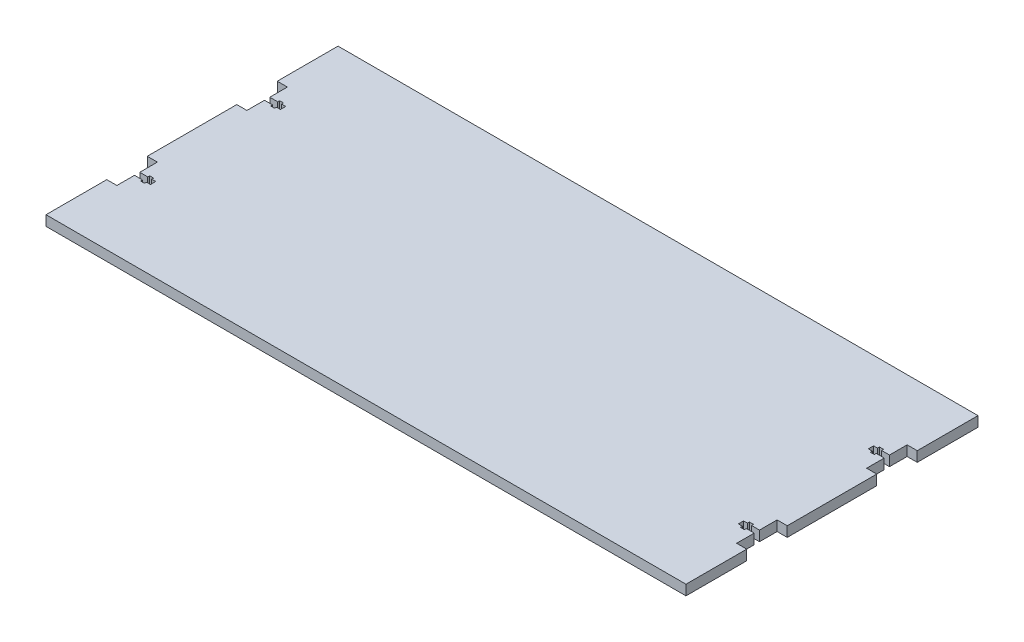
SolidWorks part; units mm, degrees
material "Pine"
ref_plane "Front Plane" through (0, 0, 0) normal (0, 0, 1) x (1, 0, 0)
ref_plane "Top Plane" through (0, 0, 0) normal (0, 1, 0) x (1, 0, 0)
ref_plane "Right Plane" through (0, 0, 0) normal (1, 0, 0) x (0, 0, -1)
ref_plane "Plane1" through (0, 365.1, 0) normal (0, -1, 0) x (1, 0, 0)
sketch "Sketch1" plane through (0, 365.1, 0) normal (0, -1, 0) x (1, 0, 0)
  line L0 (-388.62, -123.4119) -> (-382.27, -123.4119)
  line L1 (-382.27, -123.4119) -> (-382.27, -134.4619)
  line L2 (-382.27, -134.4619) -> (-377.27, -134.4619)
  line L3 (-377.27, -134.4619) -> (-377.27, -133.2619)
  line L4 (-377.27, -133.2619) -> (-374.77, -133.2619)
  line L5 (-374.77, -133.2619) -> (-374.77, -134.4619)
  line L6 (-374.77, -134.4619) -> (-372.27, -134.4619)
  line L7 (-372.27, -134.4619) -> (-372.27, -137.7619)
  line L8 (-372.27, -137.7619) -> (-374.77, -137.7619)
  line L9 (-374.77, -137.7619) -> (-374.77, -138.9619)
  line L10 (-374.77, -138.9619) -> (-377.27, -138.9619)
  line L11 (-377.27, -138.9619) -> (-377.27, -137.7619)
  line L12 (-377.27, -137.7619) -> (-382.27, -137.7619)
  line L13 (-382.27, -137.7619) -> (-382.27, -148.8119)
  line L14 (-382.27, -148.8119) -> (-388.62, -148.8119)
  line L15 (-388.62, -148.8119) -> (-388.62, -186.9119)
  line L16 (-388.62, -186.9119) -> (12.7, -186.9119)
  line L17 (12.7, -186.9119) -> (12.7, -148.8119)
  line L18 (12.7, -148.8119) -> (6.35, -148.8119)
  line L19 (6.35, -148.8119) -> (6.35, -137.7619)
  line L20 (6.35, -137.7619) -> (1.35, -137.7619)
  line L21 (1.35, -137.7619) -> (1.35, -138.9619)
  line L22 (1.35, -138.9619) -> (-1.15, -138.9619)
  line L23 (-1.15, -138.9619) -> (-1.15, -137.7619)
  line L24 (-1.15, -137.7619) -> (-3.65, -137.7619)
  line L25 (-3.65, -137.7619) -> (-3.65, -134.4619)
  line L26 (-3.65, -134.4619) -> (-1.15, -134.4619)
  line L27 (-1.15, -134.4619) -> (-1.15, -133.2619)
  line L28 (-1.15, -133.2619) -> (1.35, -133.2619)
  line L29 (1.35, -133.2619) -> (1.35, -134.4619)
  line L30 (1.35, -134.4619) -> (6.35, -134.4619)
  line L31 (6.35, -134.4619) -> (6.35, -123.4119)
  line L32 (6.35, -123.4119) -> (12.7, -123.4119)
  line L33 (12.7, -123.4119) -> (12.7, -67.2883)
  line L34 (12.7, -67.2883) -> (6.35, -67.2883)
  line L35 (6.35, -67.2883) -> (6.35, -56.2383)
  line L36 (6.35, -56.2383) -> (1.35, -56.2383)
  line L37 (1.35, -56.2383) -> (1.35, -57.4383)
  line L38 (1.35, -57.4383) -> (-1.15, -57.4383)
  line L39 (-1.15, -57.4383) -> (-1.15, -56.2383)
  line L40 (-1.15, -56.2383) -> (-3.65, -56.2383)
  line L41 (-3.65, -56.2383) -> (-3.65, -52.9383)
  line L42 (-3.65, -52.9383) -> (-1.15, -52.9383)
  line L43 (-1.15, -52.9383) -> (-1.15, -51.7383)
  line L44 (-1.15, -51.7383) -> (1.35, -51.7383)
  line L45 (1.35, -51.7383) -> (1.35, -52.9383)
  line L46 (1.35, -52.9383) -> (6.35, -52.9383)
  line L47 (6.35, -52.9383) -> (6.35, -41.8883)
  line L48 (6.35, -41.8883) -> (12.7, -41.8883)
  line L49 (12.7, -41.8883) -> (12.7, -3.7883)
  line L50 (12.7, -3.7883) -> (-388.62, -3.7883)
  line L51 (-388.62, -3.7883) -> (-388.62, -41.8883)
  line L52 (-388.62, -41.8883) -> (-382.27, -41.8883)
  line L53 (-382.27, -41.8883) -> (-382.27, -52.9383)
  line L54 (-382.27, -52.9383) -> (-377.27, -52.9383)
  line L55 (-377.27, -52.9383) -> (-377.27, -51.7383)
  line L56 (-377.27, -51.7383) -> (-374.77, -51.7383)
  line L57 (-374.77, -51.7383) -> (-374.77, -52.9383)
  line L58 (-374.77, -52.9383) -> (-372.27, -52.9383)
  line L59 (-372.27, -52.9383) -> (-372.27, -56.2383)
  line L60 (-372.27, -56.2383) -> (-374.77, -56.2383)
  line L61 (-374.77, -56.2383) -> (-374.77, -57.4383)
  line L62 (-374.77, -57.4383) -> (-377.27, -57.4383)
  line L63 (-377.27, -57.4383) -> (-377.27, -56.2383)
  line L64 (-377.27, -56.2383) -> (-382.27, -56.2383)
  line L65 (-382.27, -56.2383) -> (-382.27, -67.2883)
  line L66 (-382.27, -67.2883) -> (-388.62, -67.2883)
  line L67 (-388.62, -67.2883) -> (-388.62, -123.4119)
extrude "Boss-Extrude1" add sketch "Sketch1" against normal blind 6.35
